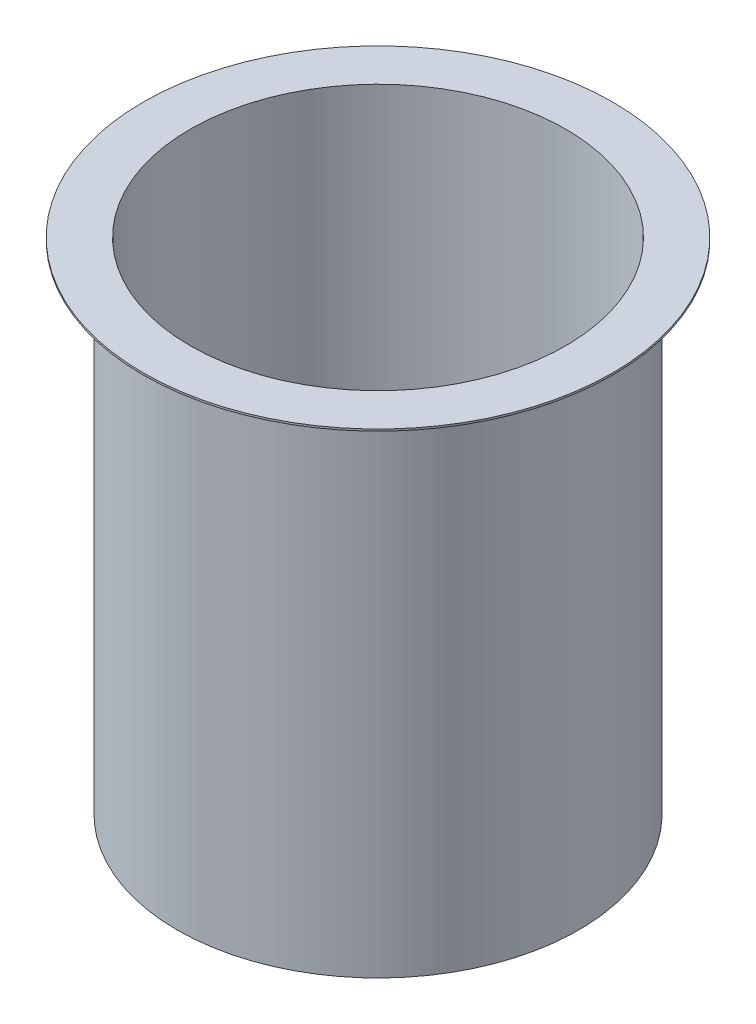
SolidWorks part; units mm, degrees
ref_plane "Front Plane" through (0, 0, 0) normal (0, 0, 1) x (1, 0, 0)
ref_plane "Top Plane" through (0, 0, 0) normal (0, 1, 0) x (1, 0, 0)
ref_plane "Right Plane" through (0, 0, 0) normal (1, 0, 0) x (0, 0, -1)
sketch "Sketch1" plane through (0, 0, 0) normal (0, 1, 0) x (1, 0, 0)
  circle A0 centre (0, 0) radius 25.4
  circle A1 centre (0, 0) radius 27.178
  dimension "D1" = 50.8
  dimension "D2" = 54.356
extrude "Boss-Extrude1" add sketch "Sketch1" along normal blind 67.31
sketch "Sketch2" plane through (0, 67.31, 0) normal (0, 1, 0) x (1, 0, 0)
  circle A0 centre (0, 0) radius 25.4
  circle A1 centre (0, 0) radius 31.75
  dimension "D1" = 6.35
extrude "Boss-Extrude2" add sketch "Sketch2" along normal blind 0.254
